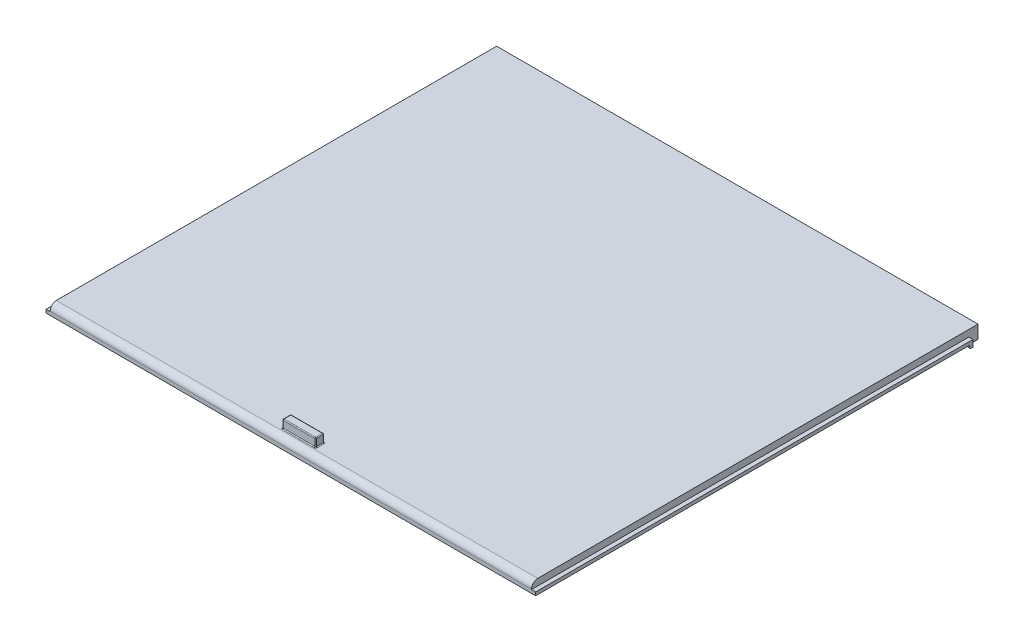
SolidWorks part; units mm, degrees
ref_plane "Front Plane" through (0, 0, 0) normal (0, 0, 1) x (1, 0, 0)
ref_plane "Top Plane" through (0, 0, 0) normal (0, 1, 0) x (1, 0, 0)
ref_plane "Right Plane" through (0, 0, 0) normal (1, 0, 0) x (0, 0, -1)
sketch "Sketch1" plane through (0, 0, 0) normal (1, 0, 0) x (0, 0, -1)
  line L0 (0, 0) -> (0, 0.4)
  line L1 (0, 0.4) -> (52.7, 0.4)
  line L5 (52.2843, 0) -> (0, 0)
  line L6 (52.2843, -0.4) -> (52.7, -0.4)
  line L7 (52.7, -0.4) -> (52.7, 0.4)
  line L8 (52.2843, 0) -> (52.2843, -0.4)
  dimension "D1" = 52.7
  dimension "D3" = 0.8
  dimension "D4" = 0.4
  dimension "D5" = 0.4157
extrude "Boss-Extrude1" add sketch "Sketch1" along normal blind 29.5
sketch "Sketch5" plane through (29.5, 0, -29.5) normal (-1, 0, 0) x (0, 0, 1)
  line L0 (29.5, 0.4) -> (-23.2, 0.4)
  line L1 (-23.2, 0.4) -> (-23.2, -0.4)
  line L2 (-23.2, -0.4) -> (-24.3, -0.4)
  line L3 (-24.3, -0.4) -> (-24.3, 1.2)
  line L4 (-24.3, 1.2) -> (29.5, 1.2)
  line L5 (29.5, 1.2) -> (29.5, 0.4)
  dimension "D1" = 0.8
  dimension "D2" = 1.1
extrude "Boss-Extrude2" add sketch "Sketch5" along normal blind 29
sketch "Sketch7" plane through (29.5, 0, 0) normal (1, 0, 0) x (0, 0, -1)
  line L5 (0, 1.2) -> (0.9961, 1.2) construction
  line L6 (0, 1.2) -> (53.8, 1.2) construction
  line L7 (0.9961, 1.2) -> (0.9961, 2.2)
  line L8 (0.9961, 2.2) -> (1.9961, 2.2)
  line L9 (1.9961, 2.2) -> (1.9961, 1.2)
  line L10 (1.9961, 1.2) -> (0.9961, 1.2)
extrude "Boss-Extrude3" add sketch "Sketch7" against normal blind 2 separate body
fillet "Fillet1" radius 0.75 1 edges at (15, 1.2, 0)
fillet "Fillet2" radius 0.2 1 edges at (14.75, -0.4, -52.2843)
mirror "Mirror1" about plane through (29.5, 0, 0) normal (-1, 0, 0) of "Boss-Extrude3", "Fillet2", "Fillet1", "Boss-Extrude2", "Boss-Extrude1"
fillet "Fillet3" radius 0.1 12 edges at (27.5, 1.2, -1.4961) (29.5, 1.2, -0.9961) (31.5, 1.2, -1.4961) (29.5, 1.2, -1.9961) (27.5, 1.7, -1.9961) (27.5, 1.7, -0.9961) (31.5, 1.7, -1.9961) (31.5, 1.7, -0.9961) (27.5, 2.2, -1.4961) (29.5, 2.2, -1.9961) (31.5, 2.2, -1.4961) (29.5, 2.2, -0.9961)
